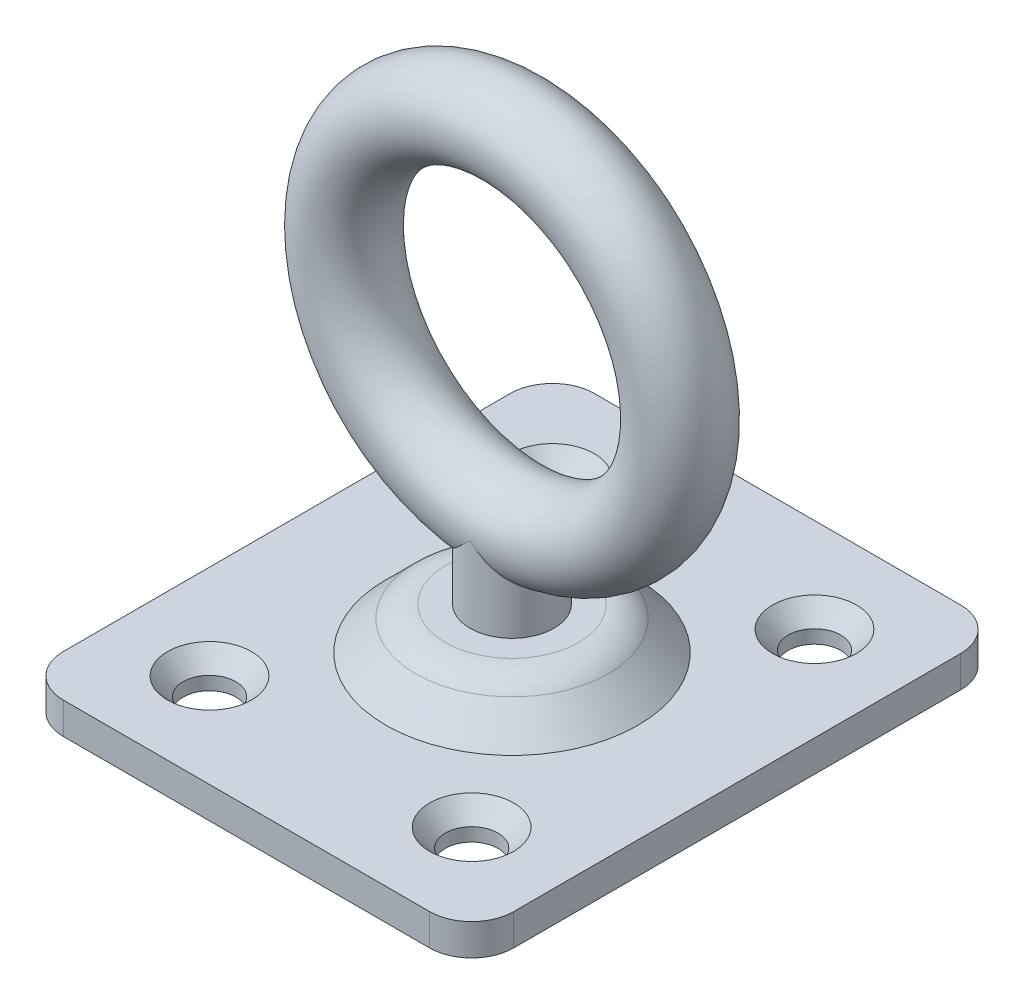
SolidWorks part; units mm, degrees
ref_plane "Front Plane" through (0, 0, 0) normal (0, 0, 1) x (1, 0, 0)
ref_plane "Top Plane" through (0, 0, 0) normal (0, 1, 0) x (1, 0, 0)
ref_plane "Right Plane" through (0, 0, 0) normal (1, 0, 0) x (0, 0, -1)
sketch "Sketch1" plane through (0, 0, 0) normal (0, 1, 0) x (1, 0, 0)
  line L0 (0, 20.066) -> (0, -20.066) construction
  line L1 (-13.843, 20.066) -> (13.843, 20.066)
  line L2 (-17.018, 16.891) -> (-17.018, -16.891)
  line L3 (-13.843, -20.066) -> (13.843, -20.066)
  line L4 (17.018, 16.891) -> (17.018, -16.891)
  line L5 (-17.018, 0) -> (17.018, 0) construction
  line L7 (-9.906, 12.954) -> (9.906, 12.954) construction
  line L8 (-9.906, 12.954) -> (-9.906, -12.954) construction
  line L9 (-9.906, -12.954) -> (9.906, -12.954) construction
  line L10 (9.906, 12.954) -> (9.906, -12.954) construction
  circle A0 centre (-9.906, 12.954) radius 1.9844 construction
  circle A1 centre (9.906, 12.954) radius 1.9844 construction
  circle A2 centre (9.906, -12.954) radius 1.9844 construction
  circle A3 centre (-9.906, -12.954) radius 1.9844 construction
  arc A4 (-13.843, 20.066) -> (-17.018, 16.891) centre (-13.843, 16.891) ccw
  arc A5 (13.843, 20.066) -> (17.018, 16.891) centre (13.843, 16.891) cw
  arc A6 (13.843, -20.066) -> (17.018, -16.891) centre (13.843, -16.891) ccw
  arc A7 (-17.018, -16.891) -> (-13.843, -20.066) centre (-13.843, -16.891) ccw
  point P12 (0, 12.954)
  point P13 (-9.906, 0)
  dimension "D5" = 3.9688
  dimension "D6" = 3.175
  dimension "D1" = 40.132
  dimension "D2" = 34.036
  dimension "D3" = 25.908
  dimension "D4" = 19.812
extrude "Boss-Extrude1" add sketch "Sketch1" along normal blind 2.3813
sketch "Sketch2" plane through (0, 0, 0) normal (0, 1, 0) x (1, 0, 0)
  circle A0 centre (-9.906, 12.954) radius 1.9844 construction
  circle A1 centre (9.906, 12.954) radius 1.9844 construction
  circle A2 centre (9.906, -12.954) radius 1.9844 construction
  circle A3 centre (-9.906, -12.954) radius 1.9844 construction
  circle A4 centre (-9.906, 12.954) radius 1.9844
  circle A5 centre (9.906, 12.954) radius 1.9844
  circle A6 centre (9.906, -12.954) radius 1.9844
  circle A7 centre (-9.906, -12.954) radius 1.9844
extrude "Cut-Extrude1" cut sketch "Sketch2" along normal up to next
sketch "Sketch3" plane through (0, 2.3813, 0) normal (0, 1, 0) x (1, 0, 0)
  circle A0 centre (-9.906, 12.954) radius 3.175
  circle A1 centre (9.906, 12.954) radius 3.175
  circle A2 centre (9.906, -12.954) radius 3.175
  circle A3 centre (-9.906, -12.954) radius 3.175
  dimension "D1" = 6.35
extrude "Cut-Extrude2" cut sketch "Sketch3" against normal through all draft 41
sketch "Sketch4" plane through (0, 0, 0) normal (0, 0, 1) x (1, 0, 0)
  line L0 (0, 0) -> (0, 39.878) construction
  line L1 (0, 33.528) -> (0, 39.878) construction
  line L2 (-9.525, 2.3812) -> (-7.2799, 4.6263)
  line L3 (-13.843, 2.3813) -> (13.843, 2.3813) construction
  line L4 (-5.0349, 5.5562) -> (0, 5.5562)
  line L5 (0, 5.5562) -> (0, 2.3813)
  line L6 (0, 2.3813) -> (-9.525, 2.3812)
  circle A0 centre (0, 24.003) radius 15.875 construction
  circle A1 centre (0, 24.003) radius 9.525 construction
  circle A2 centre (0, 36.703) radius 3.175 construction
  arc A3 (-7.2799, 4.6263) -> (-5.0349, 5.5562) centre (-5.0349, 2.3812) cw
  point P17 (-6.35, 5.5562)
  dimension "D1" = 19.05
  dimension "D3" = 6.35
  dimension "D7" = 3.175
  dimension "D2" = 39.878
  dimension "D4" = 19.05
  dimension "D5" = 12.7
  dimension "D6" = 3.175
revolve "Revolve1" add sketch "Sketch4" angle 360 mid plane about L0
sketch "Sketch5" plane through (0, 0, 0) normal (0, 0, 1) x (1, 0, 0)
  line L0 (0, 39.878) -> (0, 0) construction
  line L1 (0, 5.5562) -> (-3.175, 5.5563)
  line L2 (-3.175, 5.5563) -> (-3.175, 3.175)
  line L3 (-3.175, 5.5563) -> (-3.175, 36.703) construction
  line L4 (0, 36.703) -> (-3.175, 36.703) construction
  line L5 (17.018, 2.3813) -> (17.018, 0) construction
  line L6 (-3.175, 3.175) -> (-5.0349, 3.175)
  line L7 (-5.5961, 2.9425) -> (-7.8412, 0.6975)
  line L8 (-9.525, 2.3812) -> (-7.2799, 4.6263) construction
  line L10 (0, 0) -> (-9.525, 0)
  line L11 (0, 0) -> (0, 5.5562)
  circle A1 centre (0, 36.703) radius 3.175 construction
  arc A2 (-5.0349, 3.175) -> (-5.5961, 2.9425) centre (-5.0349, 2.3812) ccw
  arc A3 (-9.525, 0) -> (-7.8412, 0.6975) centre (-9.525, 2.3813) ccw
revolve "Cut-Revolve1" cut sketch "Sketch5" angle 360 mid plane about L0
sketch "Sketch6" plane through (0, 3.175, 0) normal (0, -1, 0) x (1, 0, 0)
  circle A0 centre (0, 0) radius 3.175 construction
  circle A1 centre (0, 0) radius 3.175
  circle A2 centre (0, 0) radius 4.7625
  dimension "D1" = 9.525
extrude "Boss-Extrude2" add sketch "Sketch6" along normal blind 1.1906 separate body
sketch "Sketch7" plane through (0, 0, 0) normal (0, 0, 1) x (1, 0, 0)
  line L0 (0, 39.878) -> (0, 0) construction
  line L1 (-3.175, 11.303) -> (-3.175, 1.9844)
  line L2 (-3.175, 5.5563) -> (-3.175, 36.703) construction
  line L3 (0, 14.478) -> (0, 8.128) construction
  line L4 (-3.175, 11.303) -> (0, 11.303)
  line L5 (-3.175, 1.9844) -> (-3.9687, 1.9844)
  line L6 (0, 11.303) -> (0, 0.7937)
  circle A0 centre (0, 24.003) radius 9.525 construction
  circle A1 centre (0, 24.003) radius 15.875 construction
  arc A2 (-3.9687, 1.9844) -> (0, 0.7937) centre (0, 8.0036) ccw
  dimension "D1" = 1.1906
  dimension "D2" = 7.9375
revolve "Revolve2" add sketch "Sketch7" angle 360 mid plane about L0
sketch "Sketch8" plane through (0, 0, 0) normal (0, 0, 1) x (1, 0, 0)
  circle A0 centre (0, 24.003) radius 12.7
sketch "Sketch9" plane through (0, 0, 0) normal (1, 0, 0) x (0, 0, -1)
  line L0 (0, 39.878) -> (0, 33.528) construction
  circle A0 centre (0, 36.703) radius 3.175
sweep "Sweep1" add profiles "Sketch9" path "Sketch8"
